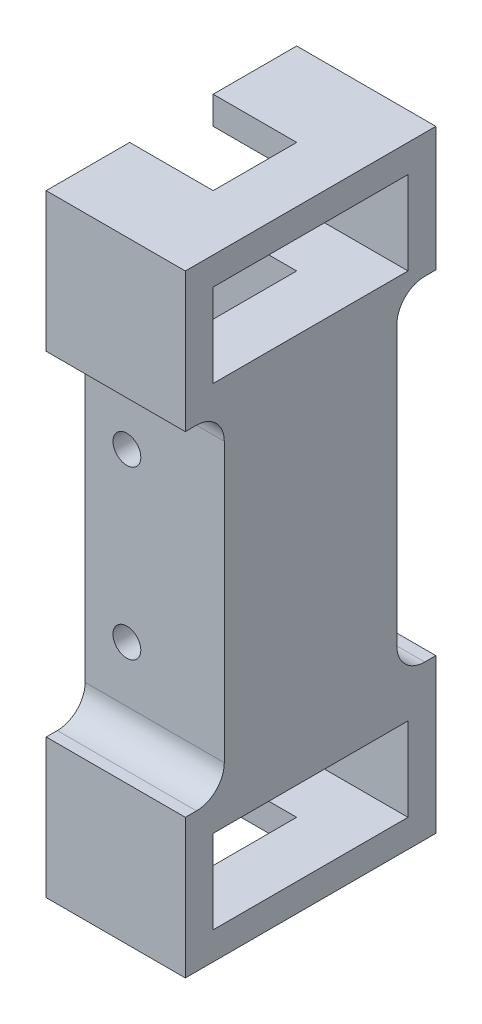
SolidWorks part; units mm, degrees
ref_plane "前视基准面" through (0, 0, 0) normal (0, 0, 1) x (1, 0, 0)
ref_plane "上视基准面" through (0, 0, 0) normal (0, 1, 0) x (1, 0, 0)
ref_plane "右视基准面" through (0, 0, 0) normal (1, 0, 0) x (0, 0, -1)
sketch "草图1" plane through (0, 0, 0) normal (0, 1, 0) x (1, 0, 0)
  line L1 (-12.5, 22.5) -> (12.5, 22.5)
  line L2 (-12.5, 22.5) -> (-12.5, -22.5)
  line L3 (-12.5, -22.5) -> (12.5, -22.5)
  line L4 (12.5, 22.5) -> (12.5, -22.5)
  line L5 (-12.5, 22.5) -> (12.5, -22.5) construction
  line L6 (-12.5, -22.5) -> (12.5, 22.5) construction
  point P0 (0, 0)
extrude "凸台-拉伸1" add sketch "草图1" along normal blind 110
sketch "草图2" plane through (0, 110, 0) normal (0, 1, 0) x (1, 0, 0)
  line L0 (0, -22.5) -> (0, 20.8988) construction
  line L1 (-12.5, -22.5) -> (12.5, -22.5) construction
  line L2 (-12.5, 22.5) -> (-12.5, -22.5) construction
  line L3 (2.5, -7.5) -> (-12.5, -7.5)
  line L4 (2.5, -7.5) -> (2.5, 7.5)
  line L5 (2.5, 7.5) -> (-12.5, 7.5)
  line L6 (-12.5, -7.5) -> (-12.5, 7.5)
  line L7 (2.5, -7.5) -> (-12.5, 7.5) construction
  line L8 (2.5, 7.5) -> (-12.5, -7.5) construction
  line L9 (12.5, 22.5) -> (-12.5, 22.5) construction
  point P5 (-5, 0)
  dimension "D1" = 22.5
extrude "切除-拉伸2" cut sketch "草图2" against normal blind 110 contours L5 L6 L3 L4
sketch "草图3" plane through (-12.5, 0, 0) normal (-1, 0, 0) x (0, 0, 1)
  line L0 (-22.5, 0) -> (-7.5, 0) construction
  line L1 (-17.5, 20) -> (17.5, 20)
  line L2 (-17.5, 20) -> (-17.5, 5)
  line L3 (-17.5, 5) -> (17.5, 5)
  line L4 (17.5, 20) -> (17.5, 5)
  line L5 (-17.5, 20) -> (17.5, 5) construction
  line L6 (-17.5, 5) -> (17.5, 20) construction
  point P0 (0, 12.5)
  dimension "D1" = 12.5
  dimension "D2" = 35
  dimension "D3" = 15
extrude "切除-拉伸3" cut sketch "草图3" against normal blind 38
sketch "草图4" plane through (-12.5, 0, 0) normal (-1, 0, 0) x (0, 0, 1)
  line L0 (17.5, 20) -> (22.5, 20) construction
  line L1 (22.5, 110) -> (22.5, 0) construction
  line L2 (17.5, 20) -> (7.5, 20) construction
  line L3 (22.5, 25) -> (15.5, 25)
  line L4 (22.5, 25) -> (22.5, 85)
  line L5 (22.5, 85) -> (15.5, 85)
  line L6 (15.5, 25) -> (15.5, 85)
  dimension "D1" = 5
  dimension "D2" = 60
extrude "切除-拉伸4" cut sketch "草图4" against normal blind 38 contours L5 L6 L3 L4
sketch "草图5" plane through (-12.5, 0, 0) normal (-1, 0, 0) x (0, 0, 1)
  line L0 (-22.5, 110) -> (-7.5, 110) construction
  line L1 (-17.5, 105) -> (17.5, 105)
  line L2 (-17.5, 105) -> (-17.5, 90)
  line L3 (-17.5, 90) -> (17.5, 90)
  line L4 (17.5, 105) -> (17.5, 90)
  line L5 (-17.5, 105) -> (17.5, 90) construction
  line L6 (-17.5, 90) -> (17.5, 105) construction
  point P0 (0, 97.5)
  dimension "D1" = 12.5
  dimension "D2" = 15
  dimension "D3" = 35
extrude "切除-拉伸5" cut sketch "草图5" against normal blind 38
fillet "圆角1" radius 5 2 edges at (0, 85, 15.5) (0, 25, 15.5)
sketch "草图6" plane through (-12.5, 0, 0) normal (-1, 0, 0) x (0, 0, 1)
  line L0 (-22.5, 110) -> (-22.5, 0) construction
  line L1 (-22.5, 27.6591) -> (-15.5, 27.6591)
  line L2 (-22.5, 27.6591) -> (-22.5, 87.6591)
  line L3 (-22.5, 87.6591) -> (-15.5, 87.6591)
  line L4 (-15.5, 27.6591) -> (-15.5, 87.6591)
  line L5 (-7.5, 20) -> (-7.5, 90) construction
  dimension "D1" = 8
extrude "切除-拉伸6" cut sketch "草图6" against normal blind 38
fillet "圆角3" radius 5 2 edges at (0, 27.6591, -15.5) (0, 87.6591, -15.5)
sketch "草图7" plane through (0, 0, -15.5) normal (0, 0, -1) x (-1, 0, 0)
  line L0 (-12.5, 110) -> (12.5, 110) construction
  line L1 (-12.5, 0) -> (12.5, 0) construction
  line L4 (12.5, 32.6591) -> (12.5, 82.6591) construction
  circle A0 centre (5, 40) radius 2.5
  circle A1 centre (5, 70) radius 2.5
  dimension "D1" = 30
  dimension "D2" = 40
  dimension "D4" = 5
  dimension "D5" = 5
  dimension "D3" = 40
  dimension "D6" = 7.5
extrude "切除-拉伸7" cut sketch "草图7" against normal blind 40
